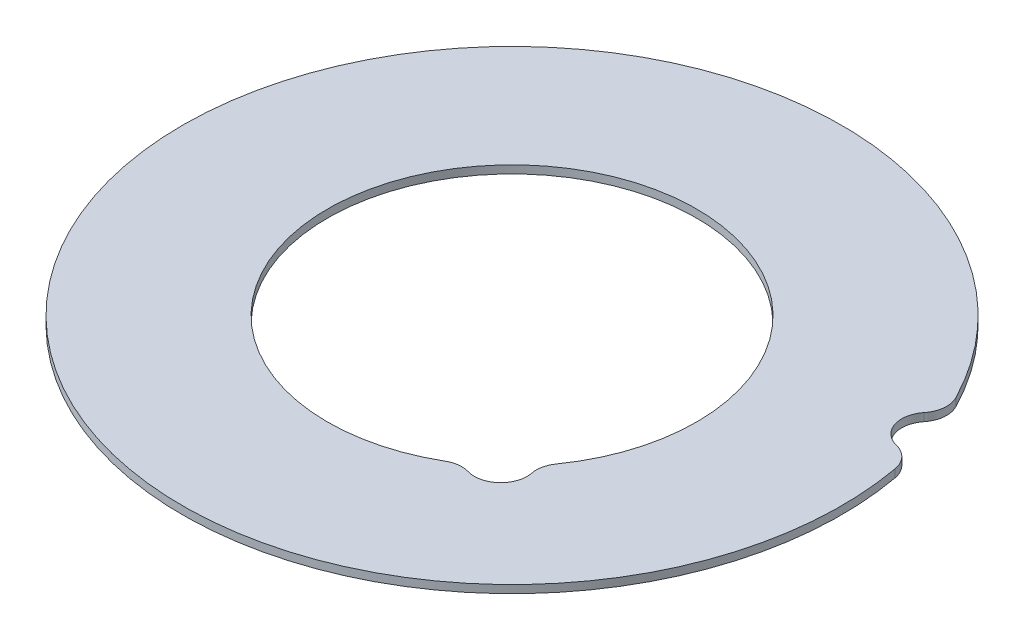
SolidWorks part; units mm, degrees
ref_plane "Front Plane" through (0, 0, 0) normal (0, 0, 1) x (1, 0, 0)
ref_plane "Top Plane" through (0, 0, 0) normal (0, 1, 0) x (1, 0, 0)
ref_plane "Right Plane" through (0, 0, 0) normal (1, 0, 0) x (0, 0, -1)
sketch "Sketch1" plane through (0, 0, 0) normal (0, 0, 1) x (1, 0, 0)
  line L0 (0, 0) -> (0, 26.6785) construction
  line L1 (-12.5, 0) -> (-12.5, 0.3)
  line L2 (-12.5, 0.3) -> (-7, 0.3)
  line L5 (-7, 0.3) -> (-7, 0)
  line L6 (-7, 0) -> (-12.5, 0)
  dimension "D1" = 5.5
  dimension "D2" = 12.5
  dimension "D3" = 0.3
revolve "Revolve1" add sketch "Sketch1" angle 360 about L0
sketch "Sketch2" plane through (0, 0.3, 0) normal (0, 1, 0) x (1, 0, 0)
  circle A0 centre (4.5711, -5) radius 1
  circle A1 centre (11.7828, 4) radius 1
  dimension "D1" = 2
extrude "Cut-Extrude1" cut sketch "Sketch2" against normal blind 10
fillet "Fillet1" radius 1 4 edges at (12.12, 0.15, -3.0586) (11.4772, 0.15, -4.9522) (3.9468, 0.15, 5.7812) (5.405, 0.15, 4.4481)
